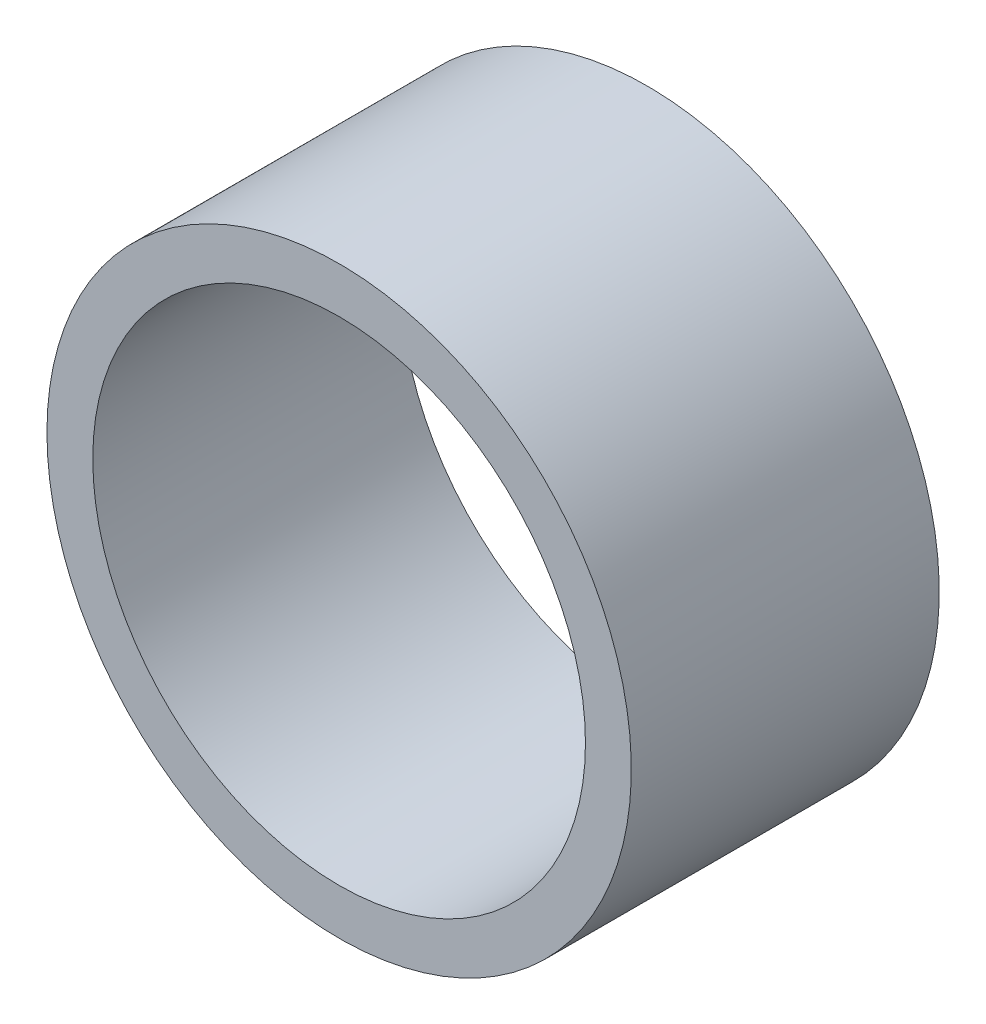
SolidWorks part; units mm, degrees
ref_plane "Front Plane" through (0, 0, 0) normal (0, 0, 1) x (1, 0, 0)
ref_plane "Top Plane" through (0, 0, 0) normal (0, 1, 0) x (1, 0, 0)
ref_plane "Right Plane" through (0, 0, 0) normal (1, 0, 0) x (0, 0, -1)
sketch "Sketch1" plane through (0, 0, 0) normal (1, 0, 0) x (0, 0, -1)
  line L0 (0, 0) -> (-7.5927, 0) construction
  line L1 (-22, 20.875) -> (-22, 17.6)
  line L4 (-22, 17.6) -> (0, 17.6)
  line L5 (0, 17.6) -> (0, 20.875)
  line L6 (0, 20.875) -> (-22, 20.875)
  dimension "D1" = 22
  dimension "D2" = 41.75
  dimension "D3" = 35.2
revolve "Revolve1" add sketch "Sketch1" angle 360 about L0
